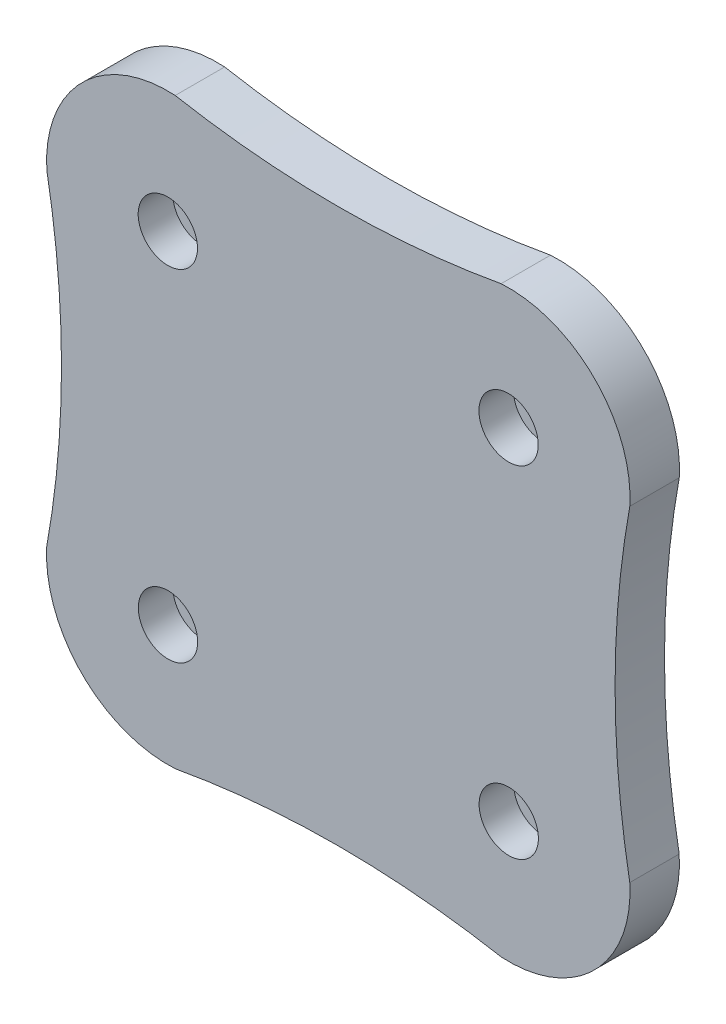
SolidWorks part; units mm, degrees
ref_plane "Front" through (0, 0, 0) normal (0, 0, 1) x (1, 0, 0)
ref_plane "Top" through (0, 0, 0) normal (0, 1, 0) x (1, 0, 0)
ref_plane "Right" through (0, 0, 0) normal (1, 0, 0) x (0, 0, -1)
sketch "Çizim1" plane through (0, 0, 0) normal (0, 1, 0) x (1, 0, 0)
  line L0 (25, -199.02) -> (25, -119.02)
  line L1 (95, -49.02) -> (175, -49.02)
  line L2 (-95, -49.02) -> (-95, -79.02)
  line L3 (-95, -79.02) -> (-15, -79.02)
  line L4 (175, -49.02) -> (175, -79.02)
  line L5 (43.7978, 40.98) -> (44.3726, -15.4825)
  line L6 (-95, -79.02) -> (9.938, -67.3602) construction
  line L7 (55, -9.02) -> (55, 70.98)
  line L8 (25, 70.98) -> (55, 70.98)
  line L9 (25, -199.02) -> (55, -199.02)
  line L10 (25, -199.02) -> (35.5417, -104.1443) construction
  line L11 (55, -199.02) -> (44.4583, -104.1443) construction
  line L12 (175, -79.02) -> (95, -79.02)
  line L13 (175, -49.02) -> (95, -49.02)
  line L14 (-95, -79.02) -> (-95, -49.02)
  line L15 (175, -79.02) -> (175, -49.02)
  line L16 (175, -79.02) -> (80.1243, -68.4783) construction
  line L17 (175, -49.02) -> (80.1243, -59.5617) construction
  line L18 (55, 70.98) -> (55, -9.02)
  line L19 (25, 70.98) -> (25, -9.02)
  line L20 (55, -199.02) -> (25, -199.02)
  line L21 (55, 70.98) -> (25, 70.98)
  line L22 (55, 70.98) -> (43.3402, -33.958) construction
  line L23 (25, 70.98) -> (36.6598, -33.958) construction
  line L24 (25, -9.02) -> (25, 70.98)
  line L25 (25, -119.02) -> (25, -199.02)
  line L26 (-15, -49.02) -> (-95, -49.02)
  line L27 (95, -79.02) -> (175, -79.02)
  line L28 (80.1243, -59.5617) -> (175, -49.02) construction
  line L29 (9.938, -67.3602) -> (-95, -79.02) construction
  line L30 (9.938, -60.6798) -> (-95, -49.02) construction
  line L31 (80.1243, -68.4783) -> (175, -79.02) construction
  line L32 (55, -119.02) -> (55, -199.02)
  line L33 (-65, -67.8178) -> (-95, -67.8178)
  line L34 (36.6598, -33.958) -> (25, 70.98) construction
  line L35 (44.4583, -104.1443) -> (55, -199.02) construction
  line L36 (35.5417, -104.1443) -> (25, -199.02) construction
  line L37 (43.3402, -33.958) -> (55, 70.98) construction
  line L38 (43.7978, 40.98) -> (43.7978, 70.98)
  line L39 (-15, -79.02) -> (-95, -79.02)
  line L40 (-95, -67.8178) -> (-95, -60.2222)
  line L41 (-65, -60.2222) -> (-95, -60.2222)
  line L42 (-65, -67.8178) -> (-95, -60.2222) construction
  line L43 (-95, -67.8178) -> (-65, -60.2222) construction
  line L44 (-65, -60.2222) -> (-8.5375, -59.6474)
  line L45 (-65, -67.8178) -> (-8.5375, -67.8178)
  line L46 (36.2022, 40.98) -> (36.2022, -15.4825)
  line L47 (36.2022, 40.98) -> (36.2022, 70.98)
  line L48 (145, -67.8178) -> (88.5375, -68.3926)
  line L49 (145, -67.8178) -> (175, -67.8178)
  line L50 (145, -60.2222) -> (88.5375, -60.2222)
  line L51 (145, -60.2222) -> (175, -60.2222)
  line L52 (36.2022, -169.02) -> (35.6274, -112.5575)
  line L53 (36.2022, -169.02) -> (36.2022, -199.02)
  line L54 (43.7978, -169.02) -> (43.7978, -112.5575)
  line L55 (43.7978, -169.02) -> (43.7978, -199.02)
  line L56 (16.0141, -40.0704) -> (29.4975, -53.5175) construction
  arc A0 (-84.8456, 25.8495) -> (-49.8695, 60.8256) centre (-95, 70.98) ccw
  circle A1 centre (40, -64.02) radius 120 construction
  circle A2 centre (-80, -64.02) radius 80
  circle A3 centre (40, -64.02) radius 120 construction
  circle A4 centre (40, 55.98) radius 80
  circle A5 centre (40, -64.02) radius 120 construction
  circle A6 centre (160, -64.02) radius 80
  circle A7 centre (40, -64.02) radius 120 construction
  circle A8 centre (40, -184.02) radius 80
  circle A9 centre (40, -184.02) radius 90 construction
  arc A10 (129.8695, 60.8256) -> (-49.8695, 60.8256) centre (40, 55.98) ccw
  arc A11 (72.6815, -42.2146) -> (72.6815, -85.8254) centre (160, -64.02) ccw
  arc A12 (61.8054, -96.7015) -> (18.1946, -96.7015) centre (40, -184.02) ccw
  arc A13 (129.8695, 60.8256) -> (164.8456, 25.8495) centre (175, 70.98) ccw
  arc A14 (164.8456, -153.8895) -> (129.8695, -188.8656) centre (175, -199.02) ccw
  arc A15 (-49.8695, -188.8656) -> (-84.8456, -153.8895) centre (-95, -199.02) ccw
  circle A16 centre (-80, -64.02) radius 15
  circle A17 centre (40, 55.98) radius 15
  circle A18 centre (160, -64.02) radius 15
  circle A19 centre (40, -184.02) radius 15
  circle A20 centre (40, 55.98) radius 90 construction
  arc A21 (95, -49.02) -> (55, -9.02) centre (95, -9.02) cw
  arc A22 (-49.8695, -188.8656) -> (129.8695, -188.8656) centre (40, -184.02) ccw
  arc A23 (164.8456, -153.8895) -> (164.8456, 25.8495) centre (160, -64.02) ccw
  arc A24 (55, -119.02) -> (95, -79.02) centre (95, -119.02) cw
  arc A25 (18.1946, -31.3385) -> (61.8054, -31.3385) centre (40, 55.98) ccw
  arc A26 (7.3185, -85.8254) -> (7.3185, -42.2146) centre (-80, -64.02) ccw
  arc A27 (-15, -79.02) -> (25, -119.02) centre (-15, -119.02) cw
  arc A28 (25, -9.02) -> (-15, -49.02) centre (-15, -9.02) cw
  arc A29 (-84.8456, 25.8495) -> (-84.8456, -153.8895) centre (-80, -64.02) ccw
  arc A30 (-8.5375, -59.6474) -> (-8.5375, -67.8178) centre (-8.5375, -63.7326) cw
  arc A31 (44.3726, -15.4825) -> (36.2022, -15.4825) centre (40.2874, -15.4825) cw
  arc A32 (88.5375, -68.3926) -> (88.5375, -60.2222) centre (88.5375, -64.3074) cw
  arc A33 (35.6274, -112.5575) -> (43.7978, -112.5575) centre (39.7126, -112.5575) cw
  arc A34 (29.4975, -53.5175) -> (50.5025, -53.5175) centre (40, 55.98) ccw
  arc A35 (29.4975, -74.5225) -> (29.4975, -53.5175) centre (-80, -64.02) ccw
  arc A36 (50.5025, -74.5225) -> (29.4975, -74.5225) centre (40, -184.02) ccw
  arc A37 (50.5025, -53.5175) -> (50.5025, -74.5225) centre (160, -64.02) ccw
  arc A38 (13.349, -50.7426) -> (66.651, -50.7426) centre (40, 55.98) ccw construction
  arc A39 (26.7226, -90.671) -> (26.7226, -37.369) centre (-80, -64.02) ccw construction
  arc A40 (53.2774, -37.369) -> (53.2774, -90.671) centre (160, -64.02) ccw construction
  arc A41 (66.651, -77.2974) -> (13.349, -77.2974) centre (40, -184.02) ccw construction
  arc A42 (16.0504, -88.0059) -> (16.0504, -40.0341) centre (-80, -64.02) ccw
  arc A43 (16.0141, -40.0704) -> (63.9859, -40.0704) centre (40, 55.98) ccw
  arc A44 (63.9496, -40.0341) -> (63.9496, -88.0059) centre (160, -64.02) ccw
  arc A45 (63.9859, -87.9696) -> (16.0141, -87.9696) centre (40, -184.02) ccw
  circle A46 centre (22.7558, -46.7939) radius 2.5
  circle A47 centre (57.2261, -46.7758) radius 2.5
  circle A48 centre (57.2442, -81.2461) radius 2.5
  circle A49 centre (22.7739, -81.2642) radius 2.5
  circle A50 centre (22.7558, -46.7939) radius 2.25
  circle A51 centre (57.2261, -46.7758) radius 2.25
  circle A52 centre (57.2442, -81.2461) radius 2.25
  circle A53 centre (22.7739, -81.2642) radius 2.25
  circle A54 centre (22.7558, -46.7939) radius 1.75
  circle A55 centre (57.2261, -46.7758) radius 1.75
  circle A56 centre (57.2442, -81.2461) radius 1.75
  circle A57 centre (22.7739, -81.2642) radius 1.75
  point P17 (40, -64.02)
  point P41 (40, -64.02)
  point P55 (40, -64.02)
  point P62 (40, -64.02)
  point P77 (40, -64.02)
  point P114 (40, -64.02)
  point P155 (40, -64.02)
  point P163 (40, -64.02)
  point P171 (40, -64.02)
  dimension "D1" = 160
  dimension "D3" = 15
  dimension "D7" = 4
  dimension "D8" = 40
  dimension "D9" = 20
  dimension "D12" = 4
  dimension "D13" = 4
  dimension "D14" = 4
  dimension "D15" = 5
  dimension "D16" = 4.5
  dimension "D17" = 3.5
  dimension "D4" = 120
  dimension "D6" = 30
  dimension "D10" = 9
  dimension "D5" = 10
  dimension "D2" = 4
  dimension "D11" = 4
sketch "Sketch1" plane through (0, 0, 0) normal (0, 0, 1) x (1, 0, 0)
  line L0 (25, -199.02) -> (25, -119.02)
  line L1 (95, -49.02) -> (175, -49.02)
  line L2 (-95, -49.02) -> (-95, -79.02)
  line L3 (-95, -79.02) -> (-15, -79.02)
  line L4 (175, -49.02) -> (175, -79.02)
  line L5 (43.7978, 40.98) -> (44.3726, -15.4825)
  line L6 (-95, -79.02) -> (9.938, -67.3602) construction
  line L7 (55, -9.02) -> (55, 70.98)
  line L8 (25, 70.98) -> (55, 70.98)
  line L9 (25, -199.02) -> (55, -199.02)
  line L10 (25, -199.02) -> (35.5417, -104.1443) construction
  line L11 (55, -199.02) -> (44.4583, -104.1443) construction
  line L12 (175, -79.02) -> (95, -79.02)
  line L13 (175, -49.02) -> (95, -49.02)
  line L14 (-95, -79.02) -> (-95, -49.02)
  line L15 (175, -79.02) -> (175, -49.02)
  line L16 (175, -79.02) -> (80.1243, -68.4783) construction
  line L17 (175, -49.02) -> (80.1243, -59.5617) construction
  line L18 (55, 70.98) -> (55, -9.02)
  line L19 (25, 70.98) -> (25, -9.02)
  line L20 (55, -199.02) -> (25, -199.02)
  line L21 (55, 70.98) -> (25, 70.98)
  line L22 (55, 70.98) -> (43.3402, -33.958) construction
  line L23 (25, 70.98) -> (36.6598, -33.958) construction
  line L24 (25, -9.02) -> (25, 70.98)
  line L25 (25, -119.02) -> (25, -199.02)
  line L26 (-15, -49.02) -> (-95, -49.02)
  line L27 (95, -79.02) -> (175, -79.02)
  line L28 (80.1243, -59.5617) -> (175, -49.02) construction
  line L29 (9.938, -67.3602) -> (-95, -79.02) construction
  line L30 (9.938, -60.6798) -> (-95, -49.02) construction
  line L31 (80.1243, -68.4783) -> (175, -79.02) construction
  line L32 (55, -119.02) -> (55, -199.02)
  line L33 (-65, -67.8178) -> (-95, -67.8178)
  line L34 (36.6598, -33.958) -> (25, 70.98) construction
  line L35 (44.4583, -104.1443) -> (55, -199.02) construction
  line L36 (35.5417, -104.1443) -> (25, -199.02) construction
  line L37 (43.3402, -33.958) -> (55, 70.98) construction
  line L38 (43.7978, 40.98) -> (43.7978, 70.98)
  line L39 (-15, -79.02) -> (-95, -79.02)
  line L40 (-95, -67.8178) -> (-95, -60.2222)
  line L41 (-65, -60.2222) -> (-95, -60.2222)
  line L42 (-65, -67.8178) -> (-95, -60.2222) construction
  line L43 (-95, -67.8178) -> (-65, -60.2222) construction
  line L44 (-65, -60.2222) -> (-8.5375, -59.6474)
  line L45 (-65, -67.8178) -> (-8.5375, -67.8178)
  line L46 (36.2022, 40.98) -> (36.2022, -15.4825)
  line L47 (36.2022, 40.98) -> (36.2022, 70.98)
  line L48 (145, -67.8178) -> (88.5375, -68.3926)
  line L49 (145, -67.8178) -> (175, -67.8178)
  line L50 (145, -60.2222) -> (88.5375, -60.2222)
  line L51 (145, -60.2222) -> (175, -60.2222)
  line L52 (36.2022, -169.02) -> (35.6274, -112.5575)
  line L53 (36.2022, -169.02) -> (36.2022, -199.02)
  line L54 (43.7978, -169.02) -> (43.7978, -112.5575)
  line L55 (43.7978, -169.02) -> (43.7978, -199.02)
  line L56 (16.0141, -40.0704) -> (16.0744, -40.1306) construction
  line L57 (20.9856, -45.0285) -> (29.4975, -53.5175) construction
  arc A0 (-84.8456, 25.8495) -> (-49.8695, 60.8256) centre (-95, 70.98) ccw
  circle A1 centre (40, -64.02) radius 120 construction
  circle A2 centre (-80, -64.02) radius 80
  circle A3 centre (40, -64.02) radius 120 construction
  circle A4 centre (40, 55.98) radius 80
  circle A5 centre (40, -64.02) radius 120 construction
  circle A6 centre (160, -64.02) radius 80
  circle A7 centre (40, -64.02) radius 120 construction
  circle A8 centre (40, -184.02) radius 80
  circle A9 centre (40, -184.02) radius 90 construction
  arc A10 (129.8695, 60.8256) -> (-49.8695, 60.8256) centre (40, 55.98) ccw
  arc A11 (72.6815, -42.2146) -> (72.6815, -85.8254) centre (160, -64.02) ccw
  arc A12 (61.8054, -96.7015) -> (18.1946, -96.7015) centre (40, -184.02) ccw
  arc A13 (129.8695, 60.8256) -> (164.8456, 25.8495) centre (175, 70.98) ccw
  arc A14 (164.8456, -153.8895) -> (129.8695, -188.8656) centre (175, -199.02) ccw
  arc A15 (-49.8695, -188.8656) -> (-84.8456, -153.8895) centre (-95, -199.02) ccw
  circle A16 centre (-80, -64.02) radius 15
  circle A17 centre (40, 55.98) radius 15
  circle A18 centre (160, -64.02) radius 15
  circle A19 centre (40, -184.02) radius 15
  circle A20 centre (40, 55.98) radius 90 construction
  arc A21 (95, -49.02) -> (55, -9.02) centre (95, -9.02) cw
  arc A22 (-49.8695, -188.8656) -> (129.8695, -188.8656) centre (40, -184.02) ccw
  arc A23 (164.8456, -153.8895) -> (164.8456, 25.8495) centre (160, -64.02) ccw
  arc A24 (55, -119.02) -> (95, -79.02) centre (95, -119.02) cw
  arc A25 (18.1946, -31.3385) -> (61.8054, -31.3385) centre (40, 55.98) ccw
  arc A26 (7.3185, -85.8254) -> (7.3185, -42.2146) centre (-80, -64.02) ccw
  arc A27 (-15, -79.02) -> (25, -119.02) centre (-15, -119.02) cw
  arc A28 (25, -9.02) -> (-15, -49.02) centre (-15, -9.02) cw
  arc A29 (-84.8456, 25.8495) -> (-84.8456, -153.8895) centre (-80, -64.02) ccw
  arc A30 (-8.5375, -59.6474) -> (-8.5375, -67.8178) centre (-8.5375, -63.7326) cw
  arc A31 (44.3726, -15.4825) -> (36.2022, -15.4825) centre (40.2874, -15.4825) cw
  arc A32 (88.5375, -68.3926) -> (88.5375, -60.2222) centre (88.5375, -64.3074) cw
  arc A33 (35.6274, -112.5575) -> (43.7978, -112.5575) centre (39.7126, -112.5575) cw
  arc A34 (29.4975, -53.5175) -> (50.5025, -53.5175) centre (40, 55.98) ccw
  arc A35 (29.4975, -74.5225) -> (29.4975, -53.5175) centre (-80, -64.02) ccw
  arc A36 (50.5025, -74.5225) -> (29.4975, -74.5225) centre (40, -184.02) ccw
  arc A37 (50.5025, -53.5175) -> (50.5025, -74.5225) centre (160, -64.02) ccw
  arc A38 (13.349, -50.7426) -> (66.651, -50.7426) centre (40, 55.98) ccw construction
  arc A39 (26.7226, -90.671) -> (26.7226, -37.369) centre (-80, -64.02) ccw construction
  arc A40 (53.2774, -37.369) -> (53.2774, -90.671) centre (160, -64.02) ccw construction
  arc A41 (66.651, -77.2974) -> (13.349, -77.2974) centre (40, -184.02) ccw construction
  arc A42 (16.0504, -88.0059) -> (16.0624, -87.9576) centre (-80, -64.02) ccw
  arc A43 (16.0141, -40.0704) -> (16.0624, -40.0824) centre (40, 55.98) ccw
  arc A44 (63.9496, -40.0341) -> (63.9376, -40.0824) centre (160, -64.02) ccw
  arc A45 (63.9859, -87.9696) -> (63.9376, -87.9576) centre (40, -184.02) ccw
  circle A46 centre (22.7558, -46.7939) radius 2.5
  circle A47 centre (57.2261, -46.7758) radius 2.5
  circle A48 centre (57.2442, -81.2461) radius 2.5
  circle A49 centre (22.7739, -81.2642) radius 2.5
  circle A50 centre (22.7558, -46.7939) radius 2.25
  circle A51 centre (57.2261, -46.7758) radius 2.25
  circle A52 centre (57.2442, -81.2461) radius 2.25
  circle A53 centre (22.7739, -81.2642) radius 2.25
  circle A54 centre (22.7558, -46.7939) radius 1.5
  circle A55 centre (57.2261, -46.7758) radius 1.5
  circle A56 centre (57.2442, -81.2461) radius 1.5
  circle A57 centre (22.7739, -81.2642) radius 1.5
  arc A60 (16.0504, -88.0059) -> (16.0504, -40.0341) centre (-80, -64.02) ccw construction
  arc A61 (16.0624, -87.9576) -> (16.0141, -87.9696) centre (40, -184.02) ccw
  arc A62 (63.9859, -87.9696) -> (16.0141, -87.9696) centre (40, -184.02) ccw construction
  arc A66 (16.0744, -40.1306) -> (16.0504, -40.0341) centre (-80, -64.02) ccw
  arc A68 (16.0141, -40.0704) -> (63.9859, -40.0704) centre (40, 55.98) ccw construction
  arc A69 (63.9376, -40.0824) -> (63.9859, -40.0704) centre (40, 55.98) ccw
  arc A71 (63.9496, -40.0341) -> (63.9496, -88.0059) centre (160, -64.02) ccw construction
  arc A72 (63.9376, -87.9576) -> (63.9496, -88.0059) centre (160, -64.02) ccw
  arc A74 (23.5019, -34.5286) -> (56.4699, -34.5338) centre (40, 55.98) ccw
  arc A75 (69.4914, -47.5219) -> (56.4699, -34.5338) centre (57.2367, -46.7865) ccw
  arc A76 (69.4914, -47.5219) -> (69.4862, -80.4899) centre (160, -64.02) ccw
  arc A77 (56.4981, -93.5114) -> (69.4862, -80.4899) centre (57.2335, -81.2567) ccw
  arc A78 (56.4981, -93.5114) -> (23.5301, -93.5062) centre (40, -184.02) ccw
  arc A79 (10.5086, -80.5181) -> (23.5301, -93.5062) centre (22.7633, -81.2535) ccw
  arc A80 (10.5086, -80.5181) -> (10.5138, -47.5501) centre (-80, -64.02) ccw
  arc A81 (23.5019, -34.5286) -> (10.5138, -47.5501) centre (22.7665, -46.7833) ccw
  point P17 (40, -64.02)
  point P41 (40, -64.02)
  point P55 (40, -64.02)
  point P62 (40, -64.02)
  point P77 (40, -64.02)
  point P114 (40, -64.02)
  point P155 (40, -64.02)
  point P163 (40, -64.02)
  point P171 (40, -64.02)
  point P185 (40, -64.02)
  dimension "D1" = 160
  dimension "D3" = 15
  dimension "D7" = 4
  dimension "D8" = 40
  dimension "D9" = 20
  dimension "D12" = 4
  dimension "D13" = 4
  dimension "D14" = 4
  dimension "D15" = 5
  dimension "D16" = 4.5
  dimension "D17" = 3
  dimension "D4" = 120
  dimension "D6" = 30
  dimension "D10" = 9
  dimension "D5" = 10
  dimension "D2" = 4
  dimension "D11" = 4
extrude "Boss-Extrude1" add sketch "Sketch1" along normal blind 5
sketch "Sketch2" plane through (0, 0, 5) normal (0, 0, 1) x (1, 0, 0)
  line L0 (22.7558, -46.7939) -> (57.2442, -81.2461) construction
  line L1 (57.2261, -46.7758) -> (22.7739, -81.2642) construction
  circle A0 centre (22.7558, -46.7939) radius 3
  circle A1 centre (57.2261, -46.7758) radius 3
  circle A2 centre (57.2442, -81.2461) radius 3
  circle A3 centre (22.7739, -81.2642) radius 3
  point P7 (40, -64.02)
  point P19 (40, -64.02)
  dimension "D1" = 6
  dimension "D2" = 4
extrude "Cut-Extrude2" cut sketch "Sketch2" against normal blind 3.5
